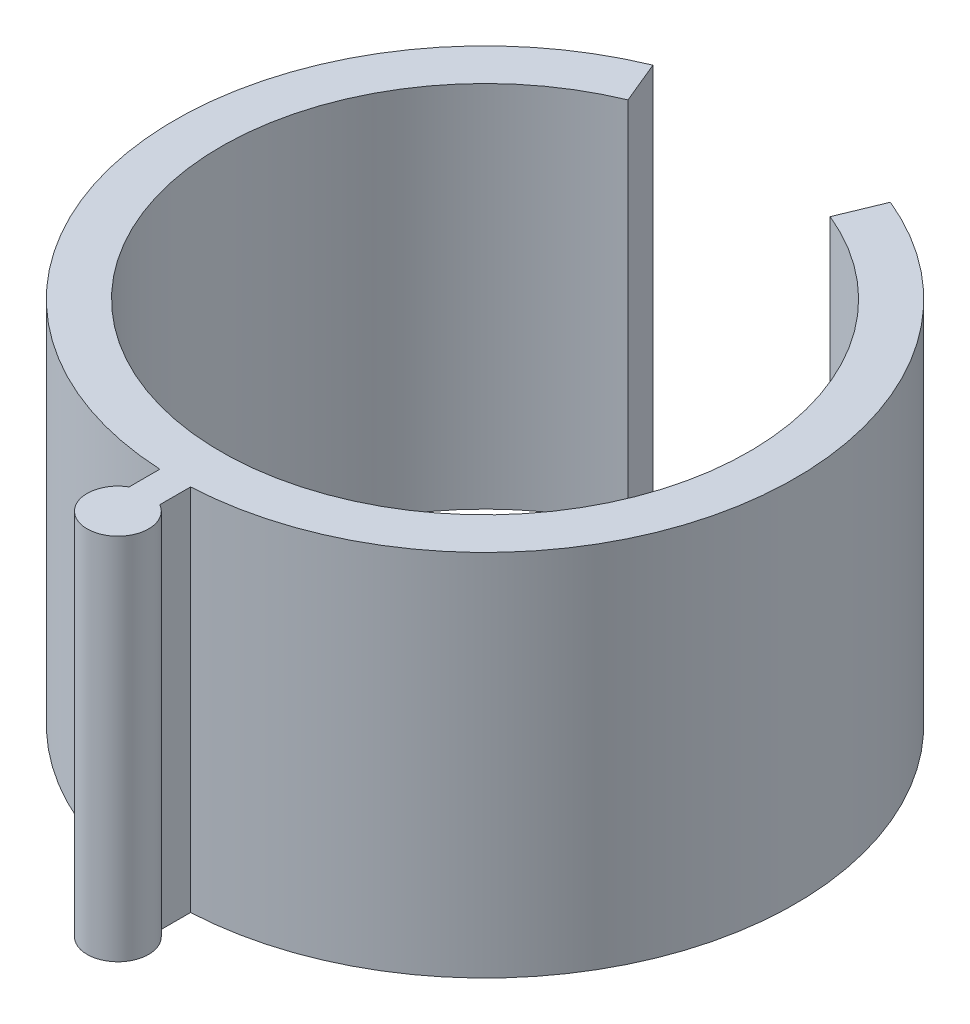
SolidWorks part; units mm, degrees
ref_plane "Front Plane" through (0, 0, 0) normal (0, 0, 1) x (1, 0, 0)
ref_plane "Top Plane" through (0, 0, 0) normal (0, 1, 0) x (1, 0, 0)
ref_plane "Right Plane" through (0, 0, 0) normal (1, 0, 0) x (0, 0, -1)
sketch "Sketch1" plane through (0, 0, 0) normal (0, 1, 0) x (1, 0, 0)
  line L0 (0, 0) -> (-4.9087, 11.8506) construction
  line L1 (0, 0) -> (4.9087, 11.8506) construction
  line L2 (0, 0) -> (0, 5.9253) construction
  line L3 (-2.4543, 5.9253) -> (2.4543, 5.9253) construction
  line L4 (-4.9087, 11.8506) -> (-4.1797, 10.0906)
  line L5 (4.9087, 11.8506) -> (4.1797, 10.0906)
  line L6 (-0.635, -12.8113) -> (-0.635, -14.0813)
  line L7 (0, 0) -> (0, -15.1811) construction
  line L8 (0.635, -12.8113) -> (0.635, -14.0813)
  line L9 (-0.635, -13.4463) -> (0.635, -13.4463) construction
  arc A0 (-4.1797, 10.0906) -> (4.1797, 10.0906) centre (0, 0) ccw
  arc A1 (-4.9087, 11.8506) -> (-0.635, -12.8113) centre (0, 0) ccw
  arc A2 (-0.635, -14.0813) -> (0.635, -14.0813) centre (0, -15.1811) ccw
  arc A3 (0.635, -12.8113) -> (4.9087, 11.8506) centre (0, 0) ccw
  point P9 (0, 5.9253)
  point P14 (0, 0)
  point P17 (0, -13.4463)
  point P18 (0, -14.4789)
  point P21 (0, -14.8856)
  dimension "D1" = 21.844
  dimension "D2" = 1.905
  dimension "D4" = 1.27
  dimension "D3" = 45
  dimension "D5" = 1.27
  dimension "D6" = 1.27
extrude "Boss-Extrude1" add sketch "Sketch1" along normal blind 15.24
